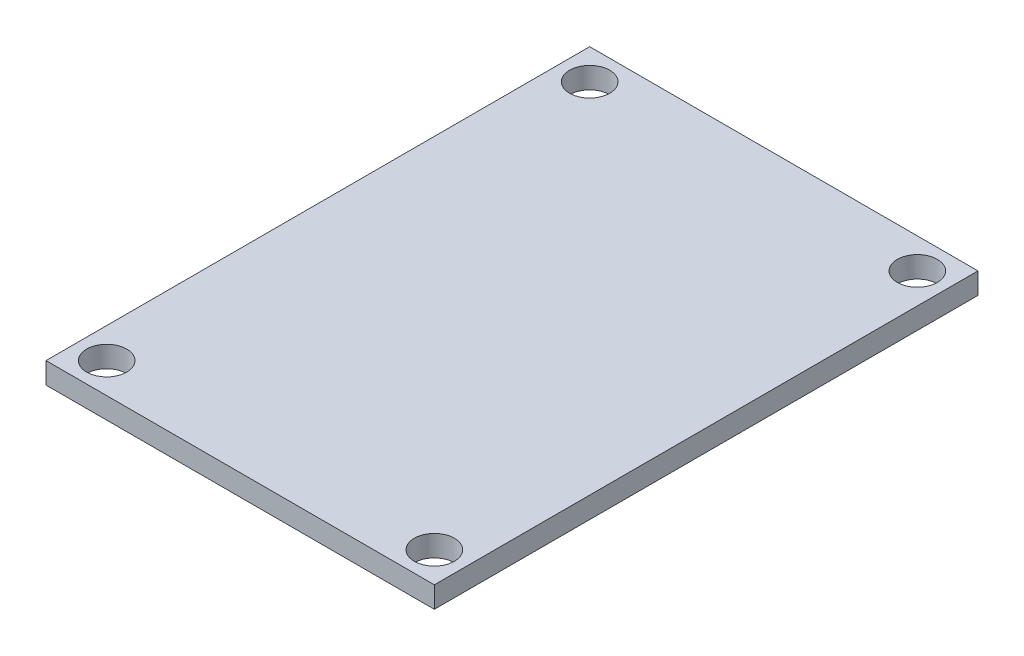
SolidWorks part; units mm, degrees
ref_plane "Alzado" through (0, 0, 0) normal (0, 0, 1) x (1, 0, 0)
ref_plane "Planta" through (0, 0, 0) normal (0, 1, 0) x (1, 0, 0)
ref_plane "Vista lateral" through (0, 0, 0) normal (1, 0, 0) x (0, 0, -1)
sketch "Croquis1" plane through (0, 0, 0) normal (0, 1, 0) x (1, 0, 0)
  line L0 (-4.2378, 0) -> (0, 0) construction
  line L1 (-16, 22.4) -> (16, 22.4)
  line L2 (-16, 22.4) -> (-16, -22.4)
  line L3 (-16, -22.4) -> (16, -22.4)
  line L4 (16, 22.4) -> (16, -22.4)
  line L5 (-16, 22.4) -> (16, -22.4) construction
  line L6 (-16, -22.4) -> (16, 22.4) construction
  line L7 (0, 0) -> (0, 6.573) construction
  line L8 (-16, 19.9) -> (-11, 19.9) construction
  line L9 (-13.5, 17.4) -> (-13.5, 22.4) construction
  circle A0 centre (-13.5, 19.9) radius 1.65
  circle A1 centre (13.5, 19.9) radius 1.65
  circle A2 centre (13.5, -19.9) radius 1.65
  circle A3 centre (-13.5, -19.9) radius 1.65
  point P0 (0, 0)
  point P14 (-13.5, 19.9)
  dimension "D4" = 3.3
  dimension "D1" = 44.8
  dimension "D2" = 32
  dimension "D3" = 5
extrude "Saliente-Extruir1" add sketch "Croquis1" along normal blind 1.75
